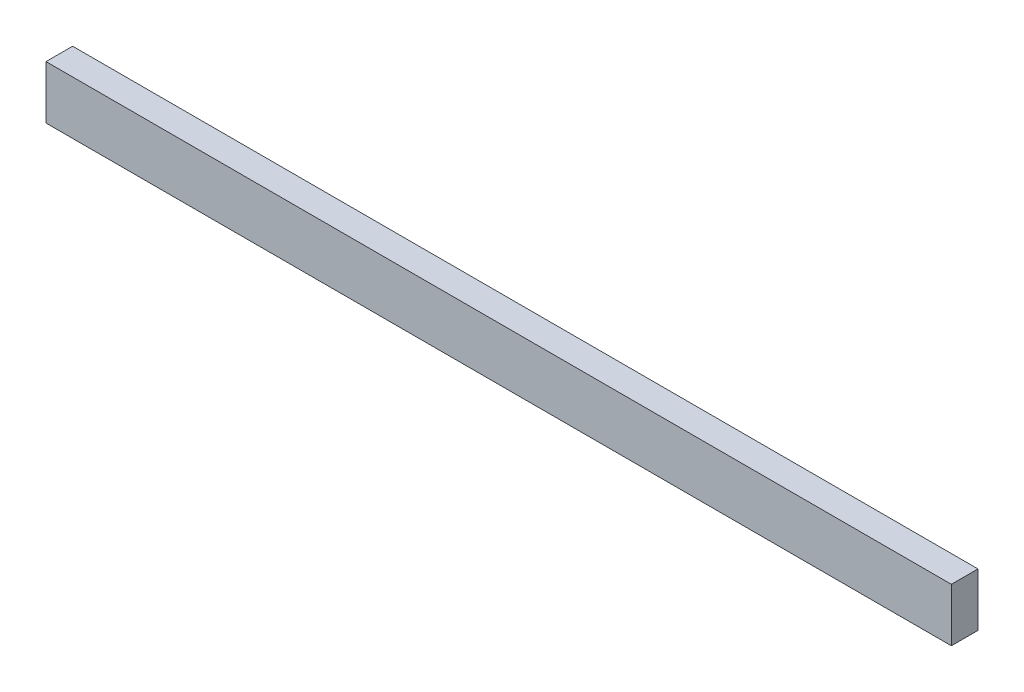
SolidWorks part; units mm, degrees
ref_plane "Спереди" through (0, 0, 0) normal (0, 0, 1) x (1, 0, 0)
ref_plane "Сверху" through (0, 0, 0) normal (0, 1, 0) x (1, 0, 0)
ref_plane "Справа" through (0, 0, 0) normal (1, 0, 0) x (0, 0, -1)
sketch "Эскиз1" plane through (0, 0, 0) normal (0, 0, 1) x (1, 0, 0)
  line L0 (0, 0) -> (170, 0)
  line L1 (170, 0) -> (170, 10)
  line L2 (170, 10) -> (0, 10)
  line L3 (0, 10) -> (0, 0)
  dimension "D1" = 170
  dimension "D2" = 10
extrude "Бобышка-Вытянуть1" add sketch "Эскиз1" along normal blind 5
